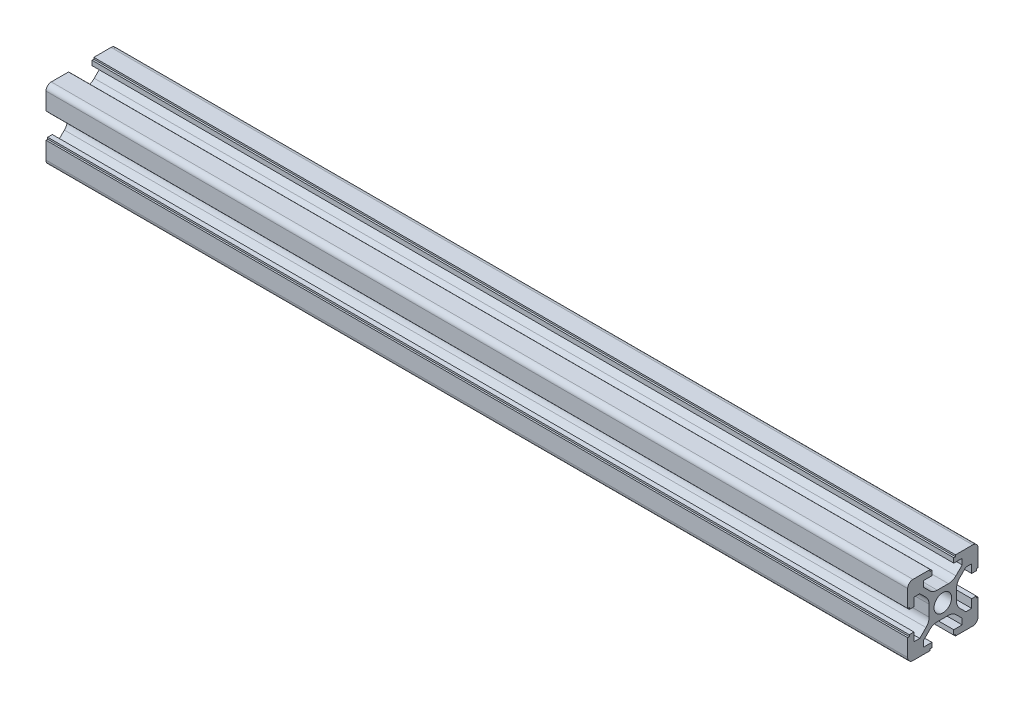
SolidWorks part; units mm, degrees
ref_plane "前视基准面" through (0, 0, 0) normal (0, 0, 1) x (1, 0, 0)
ref_plane "上视基准面" through (0, 0, 0) normal (0, 1, 0) x (1, 0, 0)
ref_plane "右视基准面" through (0, 0, 0) normal (1, 0, 0) x (0, 0, -1)
sketch "草图1" plane through (0, 0, 0) normal (1, 0, 0) x (0, 0, -1)
  line L0 (0, 0) -> (-10, 0) construction
  line L1 (0, 0) -> (0, 10) construction
  line L2 (0, 0) -> (-10, 10) construction
  line L3 (-10, 10) -> (-10, 3.6)
  line L4 (-10, 3.6) -> (-9.531, 3.6)
  line L5 (-9.531, 3.6) -> (-9.531, 3.1)
  line L6 (-9.531, 3.1) -> (-8.2, 3.1)
  line L7 (-8.2, 3.1) -> (-8.2, 5.5)
  line L8 (-8.2, 5.5) -> (-6.5607, 5.5)
  line L9 (-6.5607, 5.5) -> (-3.9, 2.8393)
  line L10 (-3.9, 2.8393) -> (-3.9, 0)
  line L11 (-3.6, 9.531) -> (-3.1, 9.531)
  line L12 (-2.8393, 3.9) -> (0, 3.9)
  line L13 (-5.5, 6.5607) -> (-2.8393, 3.9)
  line L14 (-5.5, 8.2) -> (-5.5, 6.5607)
  line L15 (-3.1, 8.2) -> (-5.5, 8.2)
  line L16 (-3.1, 9.531) -> (-3.1, 8.2)
  line L17 (-3.6, 10) -> (-3.6, 9.531)
  line L18 (-10, 10) -> (-3.6, 10)
  line L19 (0, 0) -> (0, 10) construction
  line L20 (0, 0) -> (10, 0) construction
  line L21 (0, 0) -> (10, 10) construction
  line L22 (10, 10) -> (3.6, 10)
  line L23 (3.6, 10) -> (3.6, 9.531)
  line L24 (3.6, 9.531) -> (3.1, 9.531)
  line L25 (3.1, 9.531) -> (3.1, 8.2)
  line L26 (3.1, 8.2) -> (5.5, 8.2)
  line L27 (5.5, 8.2) -> (5.5, 6.5607)
  line L28 (5.5, 6.5607) -> (2.8393, 3.9)
  line L29 (2.8393, 3.9) -> (0, 3.9)
  line L30 (9.531, 3.6) -> (9.531, 3.1)
  line L31 (3.9, 2.8393) -> (3.9, 0)
  line L32 (6.5607, 5.5) -> (3.9, 2.8393)
  line L33 (8.2, 5.5) -> (6.5607, 5.5)
  line L34 (8.2, 3.1) -> (8.2, 5.5)
  line L35 (9.531, 3.1) -> (8.2, 3.1)
  line L36 (10, 3.6) -> (9.531, 3.6)
  line L37 (10, 10) -> (10, 3.6)
  line L38 (0, 0) -> (10, 0) construction
  line L39 (0, 0) -> (0, -10) construction
  line L40 (0, 0) -> (10, -10) construction
  line L41 (10, -10) -> (10, -3.6)
  line L42 (10, -3.6) -> (9.531, -3.6)
  line L43 (9.531, -3.6) -> (9.531, -3.1)
  line L44 (9.531, -3.1) -> (8.2, -3.1)
  line L45 (8.2, -3.1) -> (8.2, -5.5)
  line L46 (8.2, -5.5) -> (6.5607, -5.5)
  line L47 (6.5607, -5.5) -> (3.9, -2.8393)
  line L48 (3.9, -2.8393) -> (3.9, 0)
  line L49 (3.6, -9.531) -> (3.1, -9.531)
  line L50 (2.8393, -3.9) -> (0, -3.9)
  line L51 (5.5, -6.5607) -> (2.8393, -3.9)
  line L52 (5.5, -8.2) -> (5.5, -6.5607)
  line L53 (3.1, -8.2) -> (5.5, -8.2)
  line L54 (3.1, -9.531) -> (3.1, -8.2)
  line L55 (3.6, -10) -> (3.6, -9.531)
  line L56 (10, -10) -> (3.6, -10)
  line L57 (0, 0) -> (0, -10) construction
  line L58 (0, 0) -> (-10, 0) construction
  line L59 (0, 0) -> (-10, -10) construction
  line L60 (-10, -10) -> (-3.6, -10)
  line L61 (-3.6, -10) -> (-3.6, -9.531)
  line L62 (-3.6, -9.531) -> (-3.1, -9.531)
  line L63 (-3.1, -9.531) -> (-3.1, -8.2)
  line L64 (-3.1, -8.2) -> (-5.5, -8.2)
  line L65 (-5.5, -8.2) -> (-5.5, -6.5607)
  line L66 (-5.5, -6.5607) -> (-2.8393, -3.9)
  line L67 (-2.8393, -3.9) -> (0, -3.9)
  line L68 (-9.531, -3.6) -> (-9.531, -3.1)
  line L69 (-3.9, -2.8393) -> (-3.9, 0)
  line L70 (-6.5607, -5.5) -> (-3.9, -2.8393)
  line L71 (-8.2, -5.5) -> (-6.5607, -5.5)
  line L72 (-8.2, -3.1) -> (-8.2, -5.5)
  line L73 (-9.531, -3.1) -> (-8.2, -3.1)
  line L74 (-10, -3.6) -> (-9.531, -3.6)
  line L75 (-10, -10) -> (-10, -3.6)
  arc A0 (0, 2.5) -> (-2.5, 0) centre (0, 0) ccw
  arc A1 (2.5, 0) -> (0, 2.5) centre (0, 0) ccw
  arc A2 (0, -2.5) -> (2.5, 0) centre (0, 0) ccw
  arc A3 (-2.5, 0) -> (0, -2.5) centre (0, 0) ccw
  point P89 (0, 0)
  dimension "D3" = 5
  dimension "D1" = 10
  dimension "D2" = 10
  dimension "D4" = 10
  dimension "D5" = 1.8
  dimension "D6" = 5.5
  dimension "D7" = 3.1
  dimension "D8" = 3.6
  dimension "D9" = 6.1
  dimension "D10" = 0.75
  dimension "D11" = 4
extrude "凸台-拉伸1" add sketch "草图1" along normal blind 245
fillet "圆角1" radius 1.5 4 edges at (122.5, -10, -10) (122.5, -10, 10) (122.5, 10, -10) (122.5, 10, 10)
fillet "圆角2" radius 3 8 edges at (122.5, -3.9, 2.8393) (122.5, -3.9, -2.8393) (122.5, -2.8393, -3.9) (122.5, 2.8393, -3.9) (122.5, 2.8393, 3.9) (122.5, -2.8393, 3.9) (122.5, 3.9, 2.8393) (122.5, 3.9, -2.8393)
